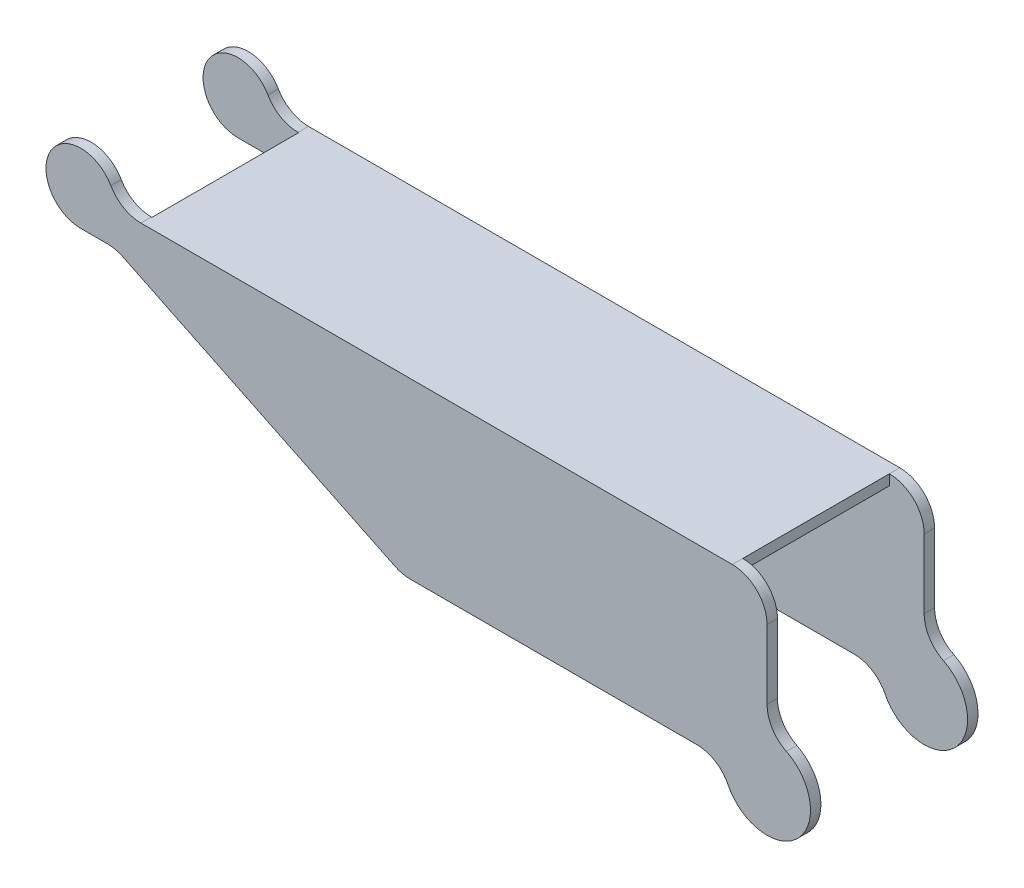
SolidWorks part; units mm, degrees
ref_plane "Alzado" through (0, 0, 0) normal (0, 0, 1) x (1, 0, 0)
ref_plane "Planta" through (0, 0, 0) normal (0, 1, 0) x (1, 0, 0)
ref_plane "Vista lateral" through (0, 0, 0) normal (1, 0, 0) x (0, 0, -1)
sketch "Croquis1" plane through (0, 0, 0) normal (0, 0, 1) x (1, 0, 0)
  line L0 (-98.745, 15) -> (-91.0415, 15)
  line L1 (-3.9535, -25) -> (78.5894, -25)
  line L3 (-81.4245, 25) -> (88.745, 25)
  line L4 (98.745, -4.8444) -> (98.745, 15)
  line L5 (-37.9788, -9.6154) -> (98.745, 25) construction
  line L6 (-98.745, 25) -> (98.745, -25) construction
  line L7 (-86.6786, 13.998) -> (-8.3164, -23.998)
  arc A0 (87.5474, -30.5556) -> (104.3006, -13.8024) centre (98.745, -25) ccw
  arc A1 (-90.0847, 30) -> (-98.745, 15) centre (-98.745, 25) ccw
  arc A2 (78.5894, -25) -> (87.5474, -30.5556) centre (78.5894, -35) cw
  arc A3 (104.3006, -13.8024) -> (98.745, -4.8444) centre (108.745, -4.8444) cw
  arc A4 (-91.0415, 15) -> (-86.6786, 13.998) centre (-91.0415, 5) cw
  arc A5 (-81.4245, 25) -> (-90.0847, 30) centre (-81.4245, 35) cw
  arc A6 (-8.3164, -23.998) -> (-3.9535, -25) centre (-3.9535, -15) ccw
  arc A7 (88.745, 25) -> (98.745, 15) centre (88.745, 15) cw
  point P0 (0, 0)
  dimension "D3" = 25
  dimension "D4" = 20
  dimension "D2" = 10
  dimension "D9" = 98.745
  dimension "D11" = 141.0377
  dimension "D1" = 197.49
  dimension "D5" = 25
  dimension "D6" = 154.132
  dimension "D7" = 25
  dimension "D10" = 98.745
extrude "Saliente-Extruir1" add sketch "Croquis1" along normal blind 3
ref_plane "Plano1" through (0, 0, -21.1) normal (0, 0, 1) x (1, 0, 0)
mirror "Simetría2" about plane through (0, 0, -21.1) normal (0, 0, 1) of bodies 101
sketch "Croquis2" plane through (0, 25, 0) normal (0, 1, 0) x (1, 0, 0)
  line L0 (-39.875, 21.1) -> (39.875, 21.1) construction
  line L1 (-81.255, 45.2) -> (88.745, 45.2)
  line L2 (-81.255, 45.2) -> (-81.255, -3)
  line L3 (-81.255, -3) -> (88.745, -3)
  line L4 (88.745, 45.2) -> (88.745, -3)
  line L5 (-81.255, 45.2) -> (88.745, -3) construction
  line L6 (-81.255, -3) -> (88.745, 45.2) construction
  point P0 (3.745, 21.1)
  dimension "D1" = 170
extrude "Saliente-Extruir2" add sketch "Croquis2" against normal blind 3
